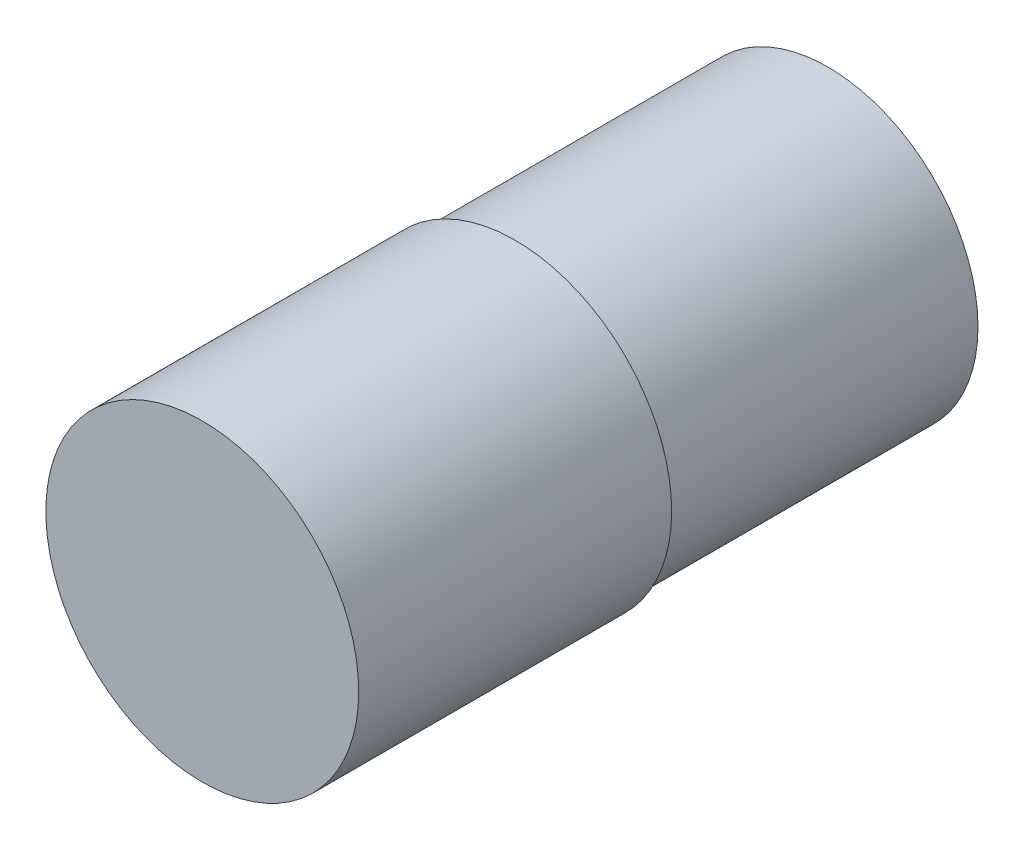
SolidWorks part; units mm, degrees
ref_plane "Front Plane" through (0, 0, 0) normal (0, 0, 1) x (1, 0, 0)
ref_plane "Top Plane" through (0, 0, 0) normal (0, 1, 0) x (1, 0, 0)
ref_plane "Right Plane" through (0, 0, 0) normal (1, 0, 0) x (0, 0, -1)
sketch "Sketch1" plane through (0, 0, 0) normal (0, 0, 1) x (1, 0, 0)
  circle A0 centre (0, 0) radius 2.3
  dimension "D1" = 4.6
extrude "Boss-Extrude1" add sketch "Sketch1" along normal blind 4.8
sketch "Sketch2" plane through (0, 0, 4.8) normal (0, 0, 1) x (1, 0, 0)
  circle A0 centre (0, 0) radius 2.4
  dimension "D1" = 4.8
extrude "Boss-Extrude2" add sketch "Sketch2" along normal blind 4.8
